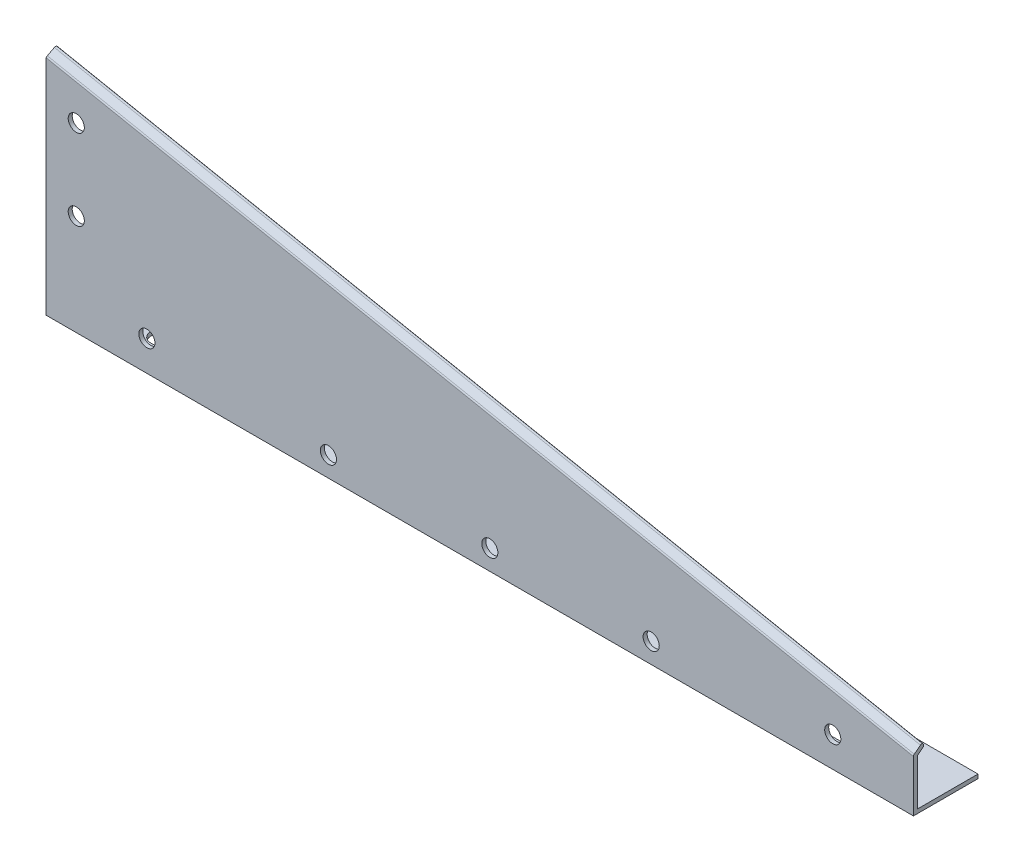
SolidWorks part; units mm, degrees
ref_plane "Front Plane" through (0, 0, 0) normal (0, 0, 1) x (1, 0, 0)
ref_plane "Top Plane" through (0, 0, 0) normal (0, 1, 0) x (1, 0, 0)
ref_plane "Right Plane" through (0, 0, 0) normal (1, 0, 0) x (0, 0, -1)
sketch "Sketch2" plane through (0, 0, 0) normal (0, 0, 1) x (1, 0, 0)
  line L0 (0, 0) -> (430, 0)
  line L1 (430, 0) -> (430, 25)
  line L2 (430, 25) -> (0, 110)
  line L3 (0, 110) -> (0, 0)
  dimension "D1" = 430
  dimension "D2" = 110
  dimension "D3" = 25
extrude "Boss-Extrude1" add sketch "Sketch2" along normal blind 2
sketch "Sketch3" plane through (0, 0, 0) normal (0, 0, -1) x (-1, 0, 0)
  line L0 (0, 110) -> (0, 0) construction
  line L1 (-430, 0) -> (0, 0)
  line L2 (-430, 0) -> (-430, 2)
  line L3 (-430, 2) -> (0, 2)
  line L4 (0, 0) -> (0, 2)
  dimension "D1" = 2
extrude "Boss-Extrude2" add sketch "Sketch3" along normal blind 30
sketch "Sketch4" plane through (0, 2, 0) normal (0, 1, 0) x (1, 0, 0)
  line L0 (215, 30) -> (215, 156.0852) construction
  line L1 (0, 30) -> (430, 30) construction
  line L2 (40, 15) -> (120, 15) construction
  line L3 (40, 20) -> (120, 20)
  line L4 (40, 10) -> (120, 10)
  line L5 (0, 30) -> (0, 0) construction
  line L6 (390, 15) -> (310, 15) construction
  line L7 (390, 20) -> (310, 20)
  line L8 (390, 10) -> (310, 10)
  arc A0 (40, 20) -> (40, 10) centre (40, 15) ccw
  arc A1 (120, 10) -> (120, 20) centre (120, 15) ccw
  arc A2 (390, 20) -> (390, 10) centre (390, 15) cw
  arc A3 (310, 10) -> (310, 20) centre (310, 15) cw
  point P6 (80, 15)
  point P16 (350, 15)
  dimension "D2" = 5
  dimension "D1" = 40
  dimension "D3" = 80
  dimension "D4" = 10
extrude "Cut-Extrude1" cut sketch "Sketch4" against normal blind 50
fillet "Fillet1" [suppressed] radius 10
sketch "Sketch7" plane through (0, 0, 2) normal (0, 0, 1) x (1, 0, 0)
  line L0 (0, 0) -> (430, 0) construction
  line L1 (0, 110) -> (0, 0) construction
  line L2 (430, 0) -> (430, 25) construction
  circle A0 centre (15, 50) radius 4
  circle A1 centre (50, 15) radius 4
  circle A2 centre (390, 15) radius 4
  circle A3 centre (15, 90) radius 4
  dimension "D3" = 8
  dimension "D4" = 8
  dimension "D5" = 8
  dimension "D10" = 8
  dimension "D1" = 50
  dimension "D2" = 15
  dimension "D6" = 15
  dimension "D7" = 50
  dimension "D8" = 15
  dimension "D9" = 40
  dimension "D11" = 90
extrude "Cut-Extrude2" cut sketch "Sketch7" against normal through all
sketch "Sketch8" plane through (0, 0, 2) normal (0, 0, 1) x (1, 0, 0)
  line L0 (140, 10) -> (220, 10) construction
  line L1 (0, 0) -> (430, 0) construction
  circle A0 centre (140, 10) radius 4
  circle A1 centre (220, 10) radius 4
  circle A2 centre (300, 10) radius 4
  circle A8 centre (50, 15) radius 4 construction
  dimension "D1" = 8
  dimension "D5" = 90
  dimension "D3" = 80
  dimension "D4" = 10
  dimension "D2" = 3
extrude "Cut-Extrude3" cut sketch "Sketch8" against normal through all
ref_plane "Plane1" through (20.9265, 105.8634, 0) normal (0.1939, 0.981, 0) x (0.981, -0.1939, 0)
ref_plane "Plane2" through (-20.9265, 4.1366, 0) normal (0.981, -0.1939, 0) x (0, 0, -1)
sketch "Sketch12" plane through (-20.9265, 4.1366, 0) normal (0.981, -0.1939, 0) x (0, 0, -1)
  line L1 (2.6685, 109.9132) -> (0, 107.9119)
  line L2 (-2, 107.9119) -> (0, 107.9119)
  line L3 (-2, 107.9119) -> (-2, 108.9119)
  line L4 (-2, 108.9119) -> (1.4685, 111.5132)
  arc A0 (1.4685, 111.5132) -> (2.6685, 109.9132) centre (2.0685, 110.7132) cw
  dimension "D1" = 2
  dimension "D3" = 1
  dimension "D2" = 5
  dimension "D4" = 1
extrude "Boss-Extrude4" add sketch "Sketch12" along normal up to surface (438.3207 mm away)
fillet "Fillet3" radius 1 2 edges at (215, 67.5, 0) (215.097, 68.5002, 2)
